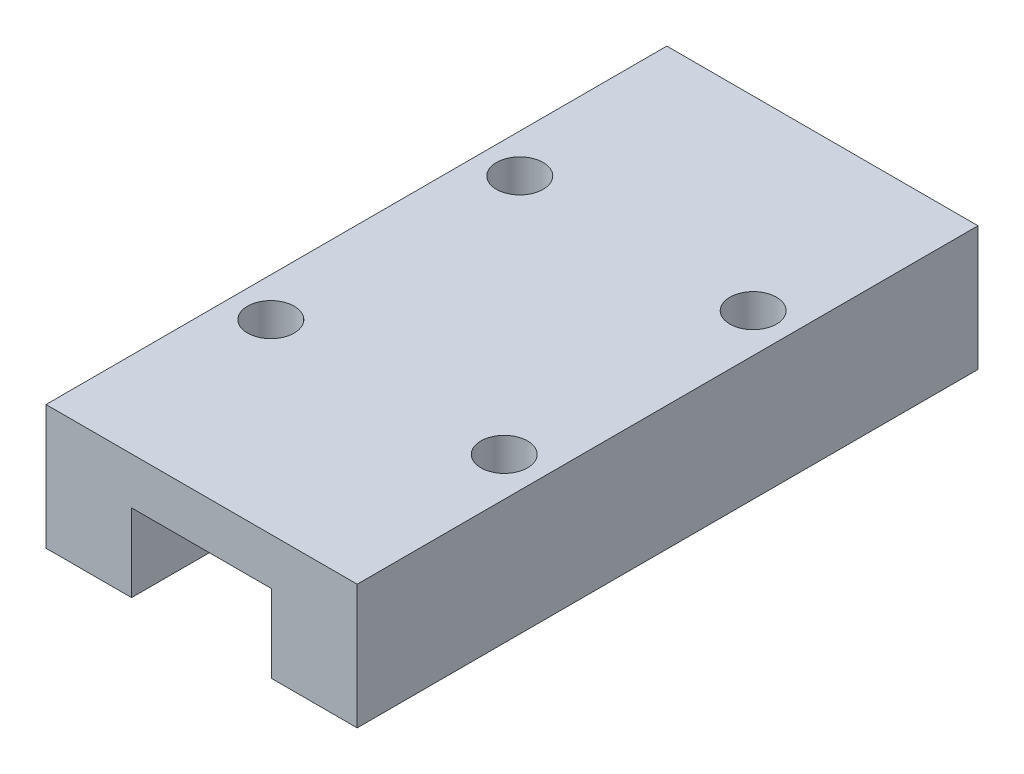
SolidWorks part; units mm, degrees
material "自定义塑料"
ref_plane "前视基准面" through (0, 0, 0) normal (0, 0, 1) x (1, 0, 0)
ref_plane "上视基准面" through (0, 0, 0) normal (0, 1, 0) x (1, 0, 0)
ref_plane "右视基准面" through (0, 0, 0) normal (1, 0, 0) x (0, 0, -1)
sketch "草图1" plane through (0, 0, 0) normal (0, 0, 1) x (1, 0, 0)
  line L0 (-10, 8) -> (-10, -5.2045) construction
  line L1 (0, 0) -> (-5.5, 0)
  line L2 (0, 0) -> (0, 8)
  line L3 (0, 8) -> (-20, 8)
  line L4 (-20, 0) -> (-20, 8)
  line L5 (-14.5, 0) -> (-14.5, 5)
  line L6 (-14.5, 5) -> (-5.5, 5)
  line L7 (-5.5, 0) -> (-5.5, 5)
  line L8 (-14.5, 0) -> (-20, 0)
  point P12 (-10, 5)
  dimension "D1" = 20
  dimension "D2" = 8
  dimension "D3" = 9
  dimension "D4" = 5
extrude "凸台-拉伸1" add sketch "草图1" along normal blind 39.9
sketch "草图2" plane through (0, 8, 0) normal (0, 1, 0) x (1, 0, 0)
  line L0 (-10, 0) -> (-10, -50000) construction
  line L1 (0, 0) -> (-20, 0) construction
  line L2 (0, -39.9) -> (-20, -39.9) construction
  line L3 (-20, -19.95) -> (49980, -19.95) construction
  line L4 (-20, -39.9) -> (-20, 0) construction
  line L5 (0, -39.9) -> (0, 0) construction
  circle A0 centre (-17.5, -11.95) radius 1.5
  circle A1 centre (-2.5, -11.95) radius 1.5
  circle A2 centre (-2.5, -27.95) radius 1.5
  circle A3 centre (-17.5, -27.95) radius 1.5
  point P4 (-10, 0)
  point P7 (-10, -39.9)
  point P16 (-20, -19.95)
  point P19 (0, -19.95)
  dimension "D3" = 3
  dimension "D1" = 15
  dimension "D2" = 16
extrude "切除-拉伸1" cut sketch "草图2" against normal blind 5
